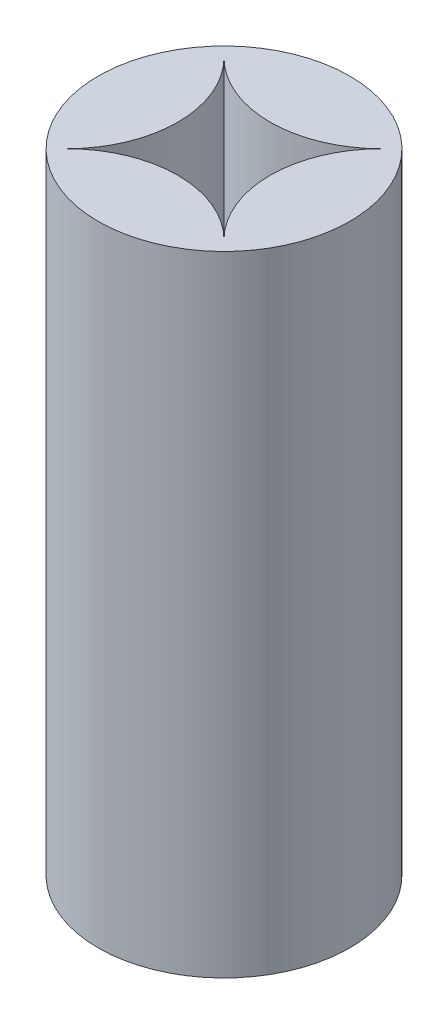
SolidWorks part; units mm, degrees
ref_plane "Front Plane" through (0, 0, 0) normal (0, 0, 1) x (1, 0, 0)
ref_plane "Top Plane" through (0, 0, 0) normal (0, 1, 0) x (1, 0, 0)
ref_plane "Right Plane" through (0, 0, 0) normal (1, 0, 0) x (0, 0, -1)
sketch "Sketch1" plane through (0, 0, 0) normal (0, 1, 0) x (1, 0, 0)
  line L5 (-2.5, -2.5) -> (2.5, 2.5) construction
  line L6 (-2.5, 2.5) -> (2.5, -2.5) construction
  circle A0 centre (0, 0) radius 4
  arc A2 (-2.5, 2.5) -> (-2.5, -2.5) centre (-5, 0) cw
  arc A3 (-2.5, 2.5) -> (2.5, 2.5) centre (0, 5) ccw
  arc A4 (2.5, -2.5) -> (2.5, 2.5) centre (5, 0) cw
  arc A5 (2.5, -2.5) -> (-2.5, -2.5) centre (0, -5) ccw
  dimension "D3" = 8
  dimension "D2" = 5
extrude "Boss-Extrude1" add sketch "Sketch1" along normal blind 20
